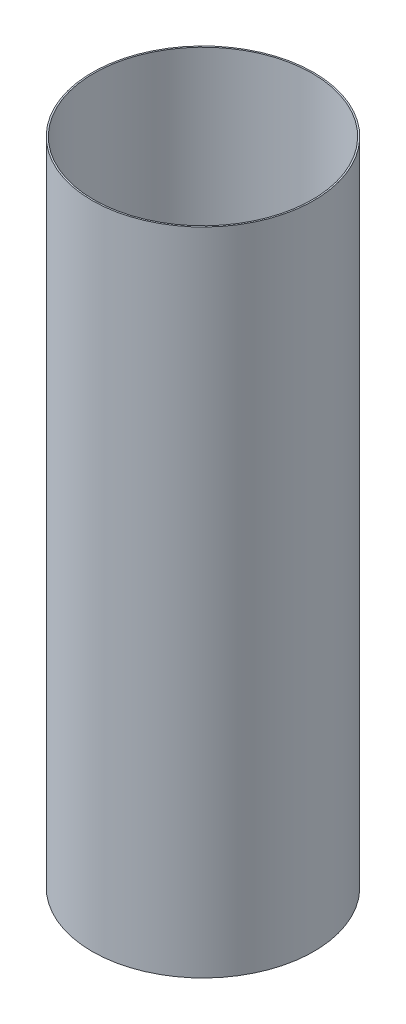
SolidWorks part; units mm, degrees
ref_plane "Front Plane" through (0, 0, 0) normal (0, 0, 1) x (1, 0, 0)
ref_plane "Top Plane" through (0, 0, 0) normal (0, 1, 0) x (1, 0, 0)
ref_plane "Right Plane" through (0, 0, 0) normal (1, 0, 0) x (0, 0, -1)
sketch "Sketch1" plane through (0, 0, 0) normal (0, 1, 0) x (1, 0, 0)
  circle A0 centre (0, 0) radius 37
  circle A1 centre (0, 0) radius 37.5
  dimension "D1" = 74
  dimension "D2" = 75
extrude "Boss-Extrude1" add sketch "Sketch1" along normal blind 220
sketch "Sketch2" plane through (0, 0, 0) normal (0, 1, 0) x (1, 0, 0)
  circle A0 centre (0, 0) radius 37.5
extrude "Boss-Extrude2" add sketch "Sketch2" along normal blind 1
